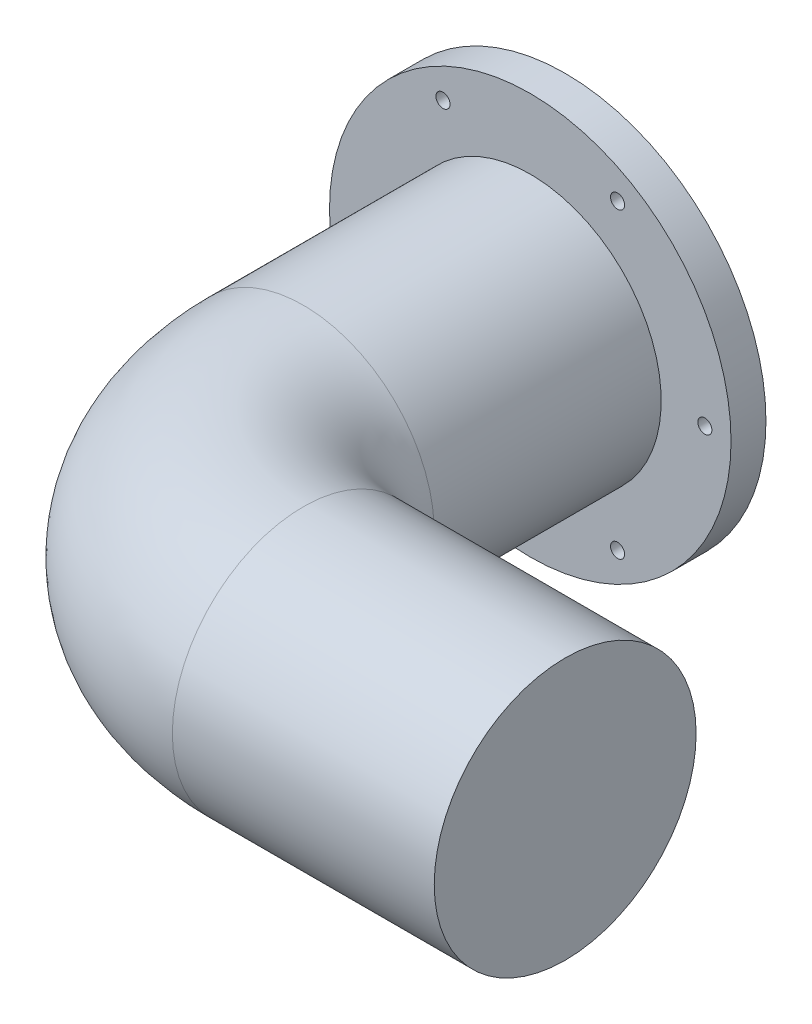
SolidWorks part; units mm, degrees
material "Plain Carbon Steel"
ref_plane "Front Plane" through (0, 0, 0) normal (0, 0, 1) x (1, 0, 0)
ref_plane "Top Plane" through (0, 0, 0) normal (0, 1, 0) x (1, 0, 0)
ref_plane "Right Plane" through (0, 0, 0) normal (1, 0, 0) x (0, 0, -1)
sketch "Sketch1" plane through (0, 0, 0) normal (0, 1, 0) x (1, 0, 0)
  line L0 (0, 0) -> (-75, 0)
  line L1 (-125, 50) -> (-125, 125)
  arc A0 (-75, 0) -> (-125, 50) centre (-75, 50) cw
  dimension "D1" = 75
  dimension "D2" = 75
  dimension "D3" = 50
  dimension "D4" = 50
sweep "Sweep1" add path "Sketch1" circular profile diameter 75 parameters "D3"=75
sketch "Sketch3" plane through (0, 0, -125) normal (0, 0, -1) x (-1, 0, 0)
  circle A0 centre (125, 0) radius 57.5
  circle A1 centre (125, 0) radius 37.5 construction
  dimension "D1" = 115
extrude "Boss-Extrude1" add sketch "Sketch3" against normal blind 10
sketch "Sketch4" plane through (0, 0, -115) normal (0, 0, 1) x (1, 0, 0)
  circle A0 centre (-125, 0) radius 50 construction
  circle A1 centre (-125, 0) radius 37.5 construction
  point P5 (-150, 43.3013)
  point P11 (-125, 0)
  point P12 (-100, 43.3013)
  point P13 (-75, 0)
  point P14 (-100, -43.3013)
  point P15 (-150, -43.3013)
  point P16 (-175, 0)
  point P17 (-125, 0)
  dimension "D1" = 100
hole_wizard "Tap Drill for #10-32 Tap1" positions "Sketch8" profile "Sketch10" hole size "#10-32" standard "ANSI Inch"
sketch "Sketch8" plane through (0, 0, -115) normal (0, 0, 1) x (1, 0, 0)
  point P12 (-150, 43.3013)
  point P15 (-175, 0)
  point P18 (-150, -43.3013)
  point P21 (-100, -43.3013)
  point P24 (-75, 0)
  point P27 (-100, 43.3013)
sketch "Sketch10" plane through (-150, 43.3013, -115) normal (1, 0, 0) x (0, -1, 0)
  line L0 (0, 0) -> (0, 10)
  line L1 (0, 10) -> (2.0193, 10)
  line L2 (2.0193, 10) -> (2.0193, 0)
  line L5 (2.0193, 0) -> (0, 0)
  line L11 (0, -6.35) -> (0, 107.95) construction
  dimension "Thru Hole Dia." = 4.0386
  dimension "Thru Hole Depth" = 10
sketch "Sketch11" plane through (0, 0, -125) normal (0, 0, -1) x (-1, 0, 0)
  line L0 (125, 0) -> (152.5, 0) construction
  line L1 (152.5, 0) -> (125, 0) construction
  circle A0 centre (125, 0) radius 27.5 construction
  circle A1 centre (125, 0) radius 57.5 construction
  circle A2 centre (152.5, 0) radius 7
  circle A3 centre (134.166, 25.9275) radius 7
  circle A4 centre (107.9093, 21.5444) radius 7
  circle A5 centre (97.667, -3.0263) radius 7
  circle A6 centre (113.0364, -24.7613) radius 7
  circle A7 centre (139.6159, -23.2943) radius 7
  point P4 (152.5, 0)
  point P5 (134.166, 25.9275)
  point P6 (107.9093, 21.5444)
  point P7 (113.0364, -24.7613)
  point P8 (139.6159, -23.2943)
  point P9 (97.667, -3.0263)
  dimension "D6" = 55
  dimension "D8" = 14
  dimension "D2" = 26.62
  dimension "D3" = 26.62
  dimension "D4" = 26.62
  dimension "D5" = 26.62
  dimension "D7" = 0
  dimension "D1" = 26.62
extrude "Cut-Extrude1" cut sketch "Sketch11" against normal blind 5
equation "\"GEARDIST\"=26.62"
equation "\"D2@Sketch11\"=\"GEARDIST\""
equation "\"D3@Sketch11\"=\"GEARDIST\""
equation "\"D4@Sketch11\"=\"GEARDIST\""
equation "\"D5@Sketch11\"=\"GEARDIST\""
equation "\"D1@Sketch11\"=\"GEARDIST\""
